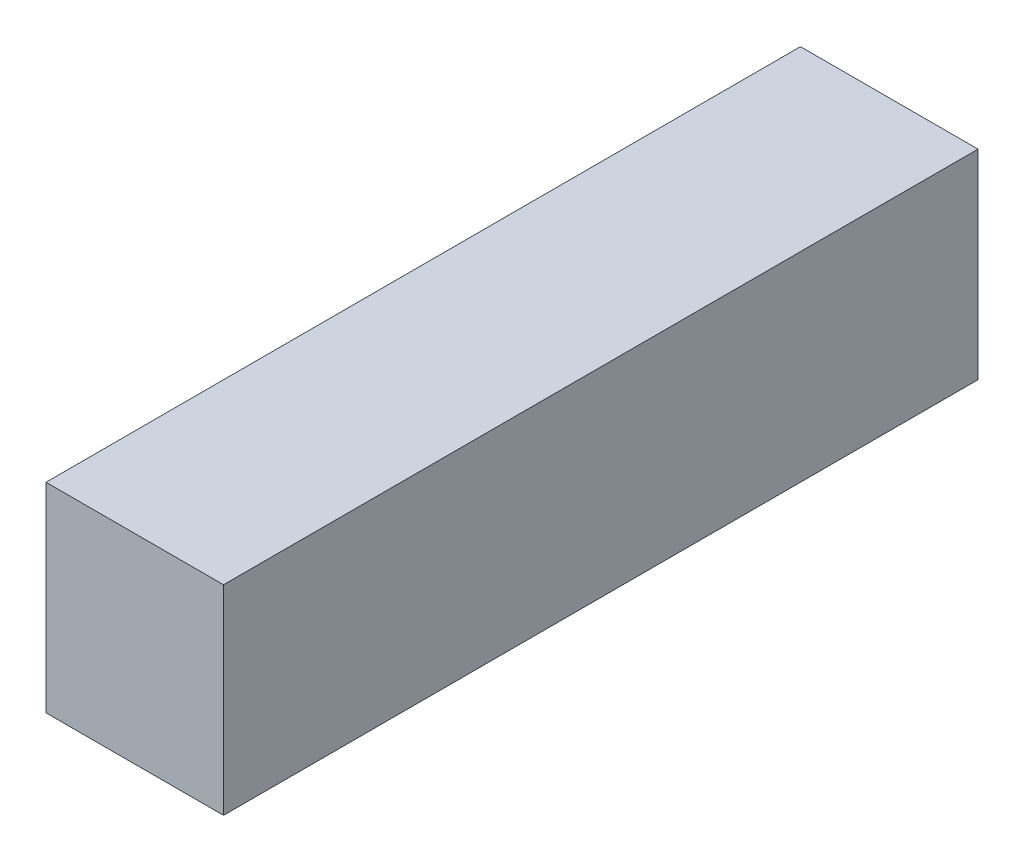
SolidWorks part; units mm, degrees
ref_plane "Front Plane" through (0, 0, 0) normal (0, 0, 1) x (1, 0, 0)
ref_plane "Top Plane" through (0, 0, 0) normal (0, 1, 0) x (1, 0, 0)
ref_plane "Right Plane" through (0, 0, 0) normal (1, 0, 0) x (0, 0, -1)
sketch "SK_P01_XT60mated" plane through (0, 0, 0) normal (0, 1, 0) x (1, 0, 0)
  line L0 (-4, -17) -> (4, -17)
  line L1 (4, -17) -> (4, 17)
  line L2 (4, 17) -> (-4, 17)
  line L3 (-4, 17) -> (-4, -17)
extrude "P01_XT60mated" add sketch "SK_P01_XT60mated" along normal blind 9
